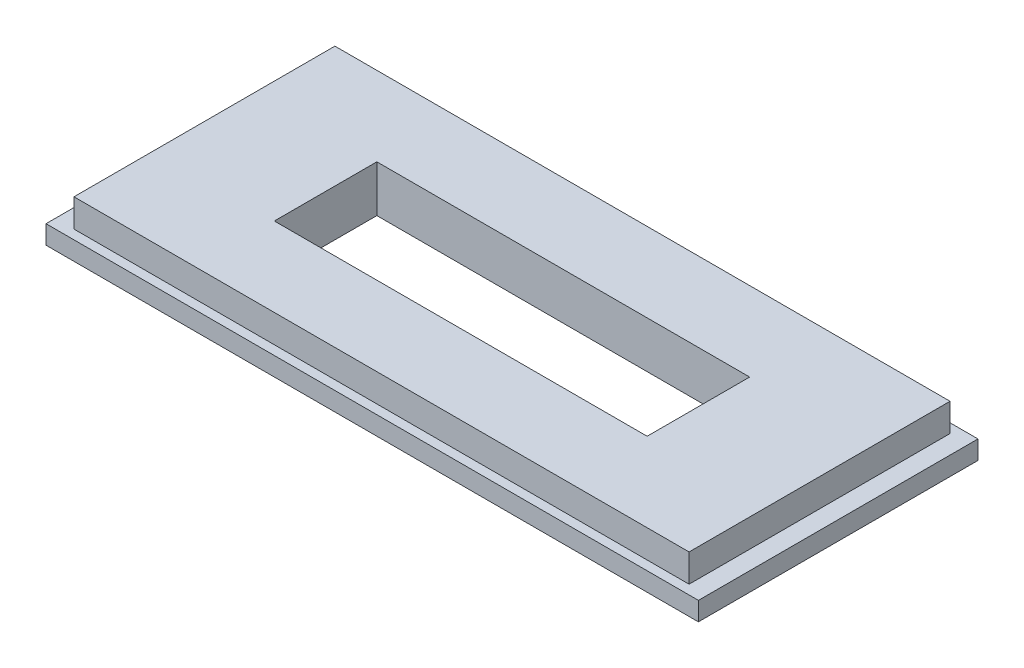
SolidWorks part; units mm, degrees
ref_plane "Front Plane" through (0, 0, 0) normal (0, 0, 1) x (1, 0, 0)
ref_plane "Top Plane" through (0, 0, 0) normal (0, 1, 0) x (1, 0, 0)
ref_plane "Right Plane" through (0, 0, 0) normal (1, 0, 0) x (0, 0, -1)
sketch "Sketch1" plane through (0, 0, 0) normal (0, 1, 0) x (1, 0, 0)
  line L1 (-35, -15) -> (35, -15)
  line L2 (-35, -15) -> (-35, 15)
  line L3 (-35, 15) -> (35, 15)
  line L4 (35, -15) -> (35, 15)
  line L5 (-35, -15) -> (35, 15) construction
  line L6 (-35, 15) -> (35, -15) construction
  point P0 (0, 0)
  dimension "D1" = 70
  dimension "D2" = 30
extrude "Boss-Extrude1" add sketch "Sketch1" along normal blind 2
sketch "Sketch2" plane through (0, 2, 0) normal (0, 1, 0) x (1, 0, 0)
  line L1 (-33, -14) -> (33, -14)
  line L2 (-33, -14) -> (-33, 14)
  line L3 (-33, 14) -> (33, 14)
  line L4 (33, -14) -> (33, 14)
  line L5 (-33, -14) -> (33, 14) construction
  line L6 (-33, 14) -> (33, -14) construction
  point P0 (0, 0)
  dimension "D1" = 66
  dimension "D2" = 28
extrude "Boss-Extrude2" add sketch "Sketch2" along normal blind 3
sketch "Sketch3" plane through (0, 5, 0) normal (0, 1, 0) x (1, 0, 0)
  line L1 (-20, -5.5) -> (20, -5.5)
  line L2 (-20, -5.5) -> (-20, 5.5)
  line L3 (-20, 5.5) -> (20, 5.5)
  line L4 (20, -5.5) -> (20, 5.5)
  line L5 (-20, -5.5) -> (20, 5.5) construction
  line L6 (-20, 5.5) -> (20, -5.5) construction
  point P0 (0, 0)
  dimension "D1" = 11
  dimension "D2" = 40
extrude "Cut-Extrude1" cut sketch "Sketch3" against normal blind 5
sketch "Sketch4" plane through (0, 0, 0) normal (0, -1, 0) x (-1, 0, 0)
  text T0 "Warning Class 4 Laser" font "Century Gothic" height 3.175
  text T1 "455nm\r\n" font "Century Gothic" height 3.175
extrude "Cut-Extrude2" cut sketch "Sketch4" against normal blind 2
